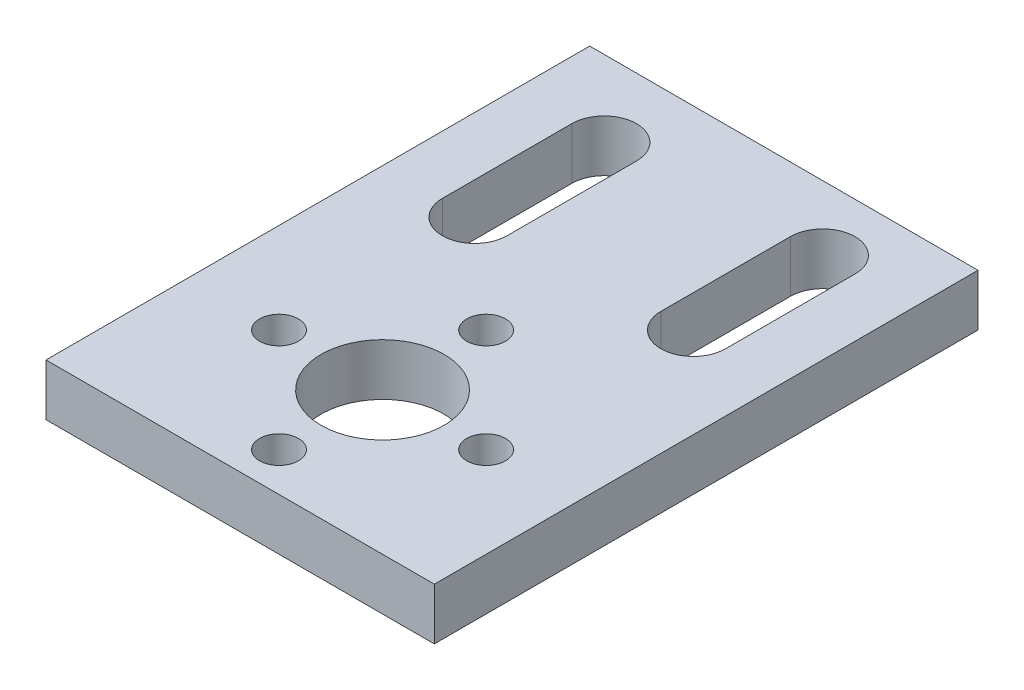
SolidWorks part; units mm, degrees
ref_plane "前视基准面" through (0, 0, 0) normal (0, 0, 1) x (1, 0, 0)
ref_plane "上视基准面" through (0, 0, 0) normal (0, 1, 0) x (1, 0, 0)
ref_plane "右视基准面" through (0, 0, 0) normal (1, 0, 0) x (0, 0, -1)
sketch "草图1" plane through (0, 0, 0) normal (0, 1, 0) x (1, 0, 0)
  line L0 (15, 0) -> (-15, 0) construction
  line L1 (15, 20) -> (-15, 20)
  line L2 (15, 20) -> (15, -22)
  line L3 (15, -22) -> (-15, -22)
  line L4 (-15, 20) -> (-15, -22)
  line L6 (-10.5, 14.1184) -> (-10.5, 4.1184)
  line L7 (-5.5, 14.1184) -> (-5.5, 4.1184)
  line L8 (5.5, 15) -> (5.5, 5)
  line L9 (10.5, 15) -> (10.5, 5)
  arc A5 (-5.5, 14.1184) -> (-10.5, 14.1184) centre (-8, 14.1184) ccw
  arc A6 (-10.5, 4.1184) -> (-5.5, 4.1184) centre (-8, 4.1184) ccw
  arc A7 (10.5, 15) -> (5.5, 15) centre (8, 15) ccw
  arc A8 (5.5, 5) -> (10.5, 5) centre (8, 5) ccw
  circle A9 centre (0, -11) radius 4.75
  circle A10 centre (0, -3) radius 1.5
  circle A14 centre (8, -11) radius 1.5
  circle A15 centre (0, -19) radius 1.5
  circle A16 centre (-8, -11) radius 1.5
  point P0 (0, 0)
  point P33 (0, -11)
  point P34 (0, -11)
  dimension "D3" = 5
  dimension "D6" = 10
  dimension "D4" = 11
  dimension "D5" = 4
  dimension "D1" = 30
  dimension "D2" = 42
  dimension "D7" = 5
  dimension "D8" = 8
extrude "凸台-拉伸1" add sketch "草图1" along normal blind 4
